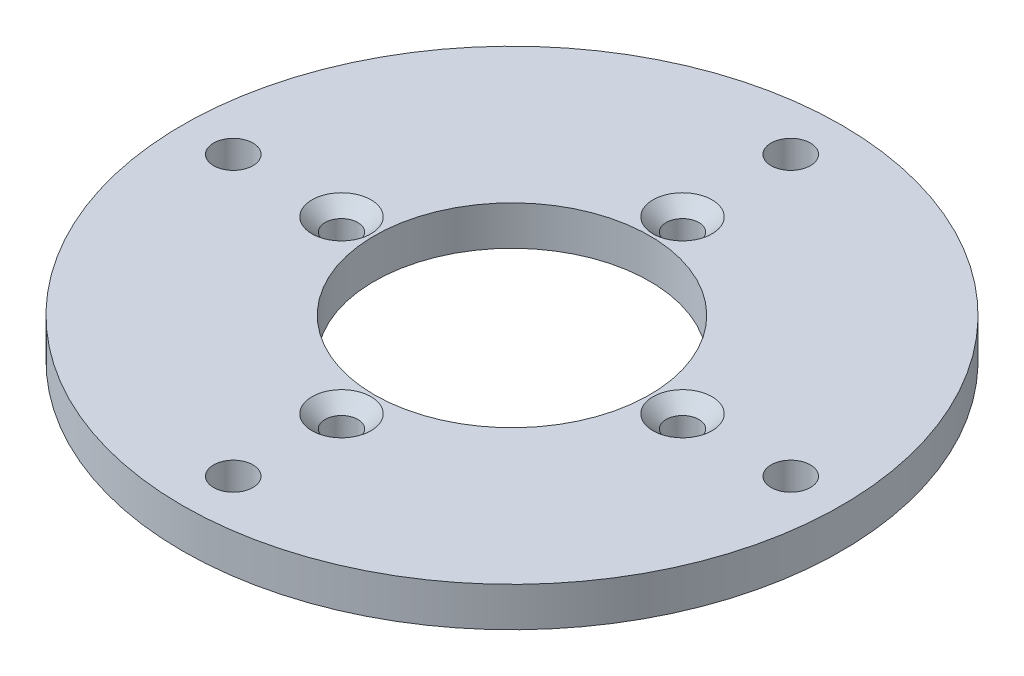
SolidWorks part; units mm, degrees
ref_plane "Спереди" through (0, 0, 0) normal (0, 0, 1) x (1, 0, 0)
ref_plane "Сверху" through (0, 0, 0) normal (0, 1, 0) x (1, 0, 0)
ref_plane "Справа" through (0, 0, 0) normal (1, 0, 0) x (0, 0, -1)
sketch "Эскиз1" plane through (0, 0, 0) normal (0, 1, 0) x (1, 0, 0)
  circle A0 centre (0, 0) radius 50.25
  circle A1 centre (0, 0) radius 21
  dimension "D1" = 100.5
  dimension "D2" = 42
extrude "Бобышка-Вытянуть1" add sketch "Эскиз1" along normal blind 6
sketch "Эскиз2" plane through (0, 6, 0) normal (0, 1, 0) x (1, 0, 0)
  line L0 (0, 26) -> (0, -26) construction
  line L2 (26, 0) -> (-26, 0) construction
  circle A0 centre (0, 0) radius 26 construction
  circle A1 centre (0, 26) radius 2.5
  circle A2 centre (-26, 0) radius 2.5
  circle A3 centre (26, 0) radius 2.5
  circle A4 centre (0, -26) radius 2.5
  dimension "D1" = 52
  dimension "D2" = 5
  dimension "D3" = 5
  dimension "D4" = 5
  dimension "D5" = 5
extrude "Вырез-Вытянуть1" cut sketch "Эскиз2" against normal blind 6
sketch "Эскиз3" plane through (0, 6, 0) normal (0, 1, 0) x (1, 0, 0)
  circle A0 centre (0, 0) radius 42.5 construction
  circle A1 centre (-42.5, 0) radius 3
  circle A2 centre (0, 42.5) radius 3
  circle A3 centre (42.5, 0) radius 3
  circle A4 centre (0, -42.5) radius 3
  dimension "D1" = 6
  dimension "D2" = 85
  dimension "D3" = 6
  dimension "D4" = 6
  dimension "D5" = 6
extrude "Вырез-Вытянуть2" cut sketch "Эскиз3" against normal blind 10
chamfer "Фаска1" distance 2 angle 45 4 edges at (0, 6, 28.5) (26, 6, 2.5) (0, 6, -23.5) (-26, 6, 2.5)
